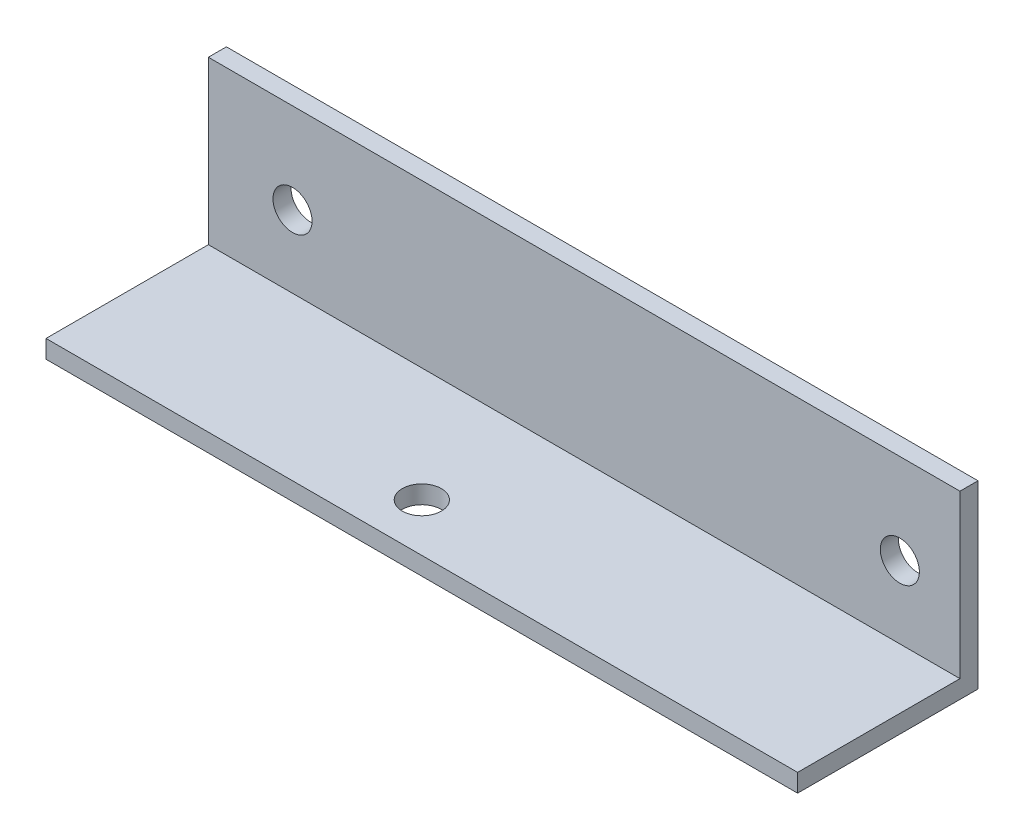
SolidWorks part; units mm, degrees
material "6061 Alloy"
ref_plane "Front Plane" through (0, 0, 0) normal (0, 0, 1) x (1, 0, 0)
ref_plane "Top Plane" through (0, 0, 0) normal (0, 1, 0) x (1, 0, 0)
ref_plane "Right Plane" through (0, 0, 0) normal (1, 0, 0) x (0, 0, -1)
sketch "Sketch1" plane through (0, 0, 0) normal (0, 0, 1) x (1, 0, 0)
  line L1 (-62.5, -15) -> (62.5, -15)
  line L2 (-62.5, -15) -> (-62.5, 15)
  line L3 (-62.5, 15) -> (62.5, 15)
  line L4 (62.5, -15) -> (62.5, 15)
  line L5 (-62.5, -15) -> (62.5, 15) construction
  line L6 (-62.5, 15) -> (62.5, -15) construction
  point P0 (0, 0)
  dimension "D1" = 125
  dimension "D2" = 30
extrude "Boss-Extrude1" add sketch "Sketch1" along normal blind 3
sketch "Sketch2" plane through (0, 0, 3) normal (0, 0, 1) x (1, 0, 0)
  line L0 (-62.5, -15) -> (62.5, -15) construction
  line L1 (-62.5, -15) -> (62.5, -15)
  line L2 (-62.5, -15) -> (-62.5, -12)
  line L3 (-62.5, 15) -> (-62.5, -15) construction
  line L4 (-62.5, -12) -> (62.5, -12)
  line L5 (62.5, -15) -> (62.5, 15) construction
  line L6 (62.5, -12) -> (62.5, -15)
  dimension "D1" = 3
extrude "Boss-Extrude2" add sketch "Sketch2" along normal blind 27
hole_wizard "Ø6.5 (6.5) Diameter Hole1" positions "Sketch3" profile "Sketch4" hole size "Ø6.5" standard "ANSI Metric"
sketch "Sketch3" plane through (0, 0, 0) normal (0, 0, -1) x (-1, 0, 0)
  line L0 (62.5, 15) -> (62.5, -12) construction
  line L1 (-62.5, 15) -> (62.5, 15) construction
  line L2 (-62.5, -12) -> (-62.5, 15) construction
  point P0 (48.5, 0)
  point P3 (-52.5, 0)
  dimension "D1" = 14
  dimension "D2" = 15
  dimension "D3" = 10
  dimension "D4" = 15
sketch "Sketch4" plane through (-48.5, 0, 0) normal (1, 0, 0) x (0, 1, 0)
  line L0 (0, 0) -> (0, 11.9528)
  line L1 (0, 11.9528) -> (3.25, 10)
  line L2 (3.25, 10) -> (3.25, 0)
  line L5 (3.25, 0) -> (0, 0)
  line L10 (0, 11.9528) -> (-3.25, 10) construction
  line L11 (0, -6.35) -> (0, 107.95) construction
  dimension "Hole Dia." = 6.5
  dimension "Hole Depth" = 10
  dimension "Drill Angle" = 118
hole_wizard "Ø6.5 (6.5) Diameter Hole2" positions "Sketch7" profile "Sketch8" hole size "Ø6.5" standard "ANSI Metric"
sketch "Sketch7" plane through (0, -15, 0) normal (0, -1, 0) x (-1, 0, 0)
  point P0 (8, -22)
sketch "Sketch8" plane through (-8, -15, 22) normal (1, 0, 0) x (0, 0, -1)
  line L0 (0, 0) -> (0, 11.9528)
  line L1 (0, 11.9528) -> (3.25, 10)
  line L2 (3.25, 10) -> (3.25, 0)
  line L5 (3.25, 0) -> (0, 0)
  line L10 (0, 11.9528) -> (-3.25, 10) construction
  line L11 (0, -6.35) -> (0, 107.95) construction
  dimension "Hole Dia." = 6.5
  dimension "Hole Depth" = 10
  dimension "Drill Angle" = 118
